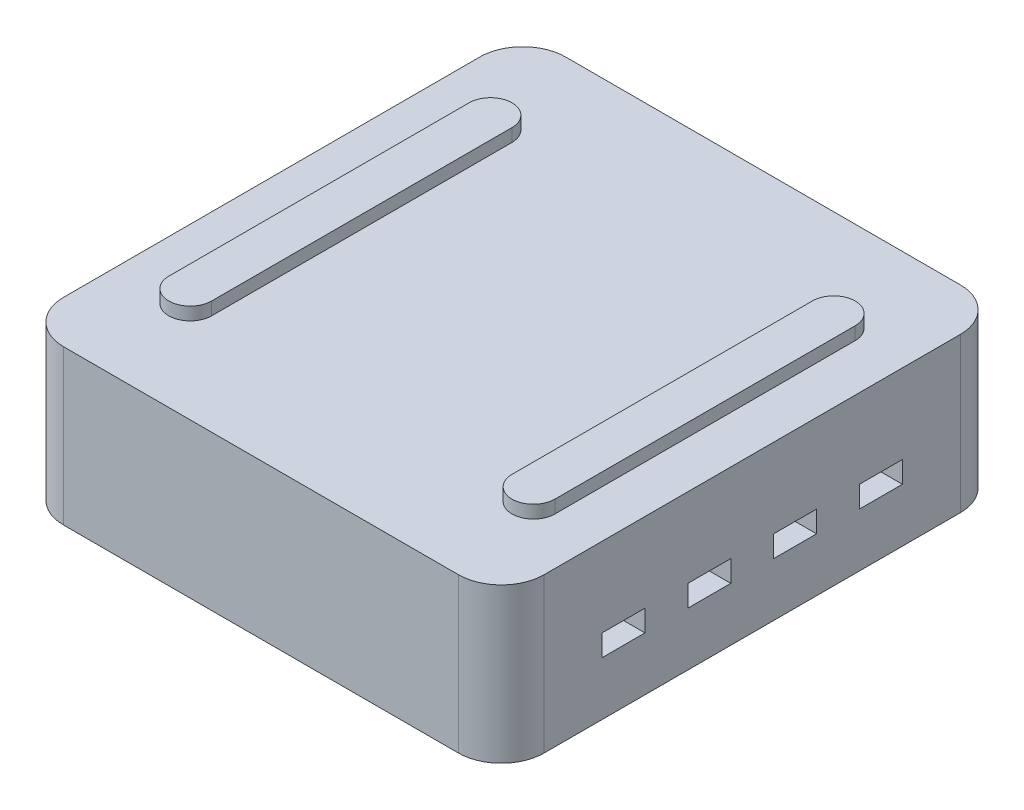
SolidWorks part; units mm, degrees
ref_plane "前视基准面" through (0, 0, 0) normal (0, 0, 1) x (1, 0, 0)
ref_plane "上视基准面" through (0, 0, 0) normal (0, 1, 0) x (1, 0, 0)
ref_plane "右视基准面" through (0, 0, 0) normal (1, 0, 0) x (0, 0, -1)
other "Configuration Table"
sketch "草图1" plane through (0, 0, 0) normal (0, 1, 0) x (1, 0, 0)
  line L1 (-56, 58.5) -> (56, 58.5)
  line L2 (-56, 58.5) -> (-56, -58.5)
  line L3 (-56, -58.5) -> (56, -58.5)
  line L4 (56, 58.5) -> (56, -58.5)
  line L5 (-56, 58.5) -> (56, -58.5) construction
  line L6 (-56, -58.5) -> (56, 58.5) construction
  point P0 (0, 0)
  dimension "D1" = 112
  dimension "D2" = 117
extrude "凸台-拉伸1" add sketch "草图1" along normal blind 36
fillet "圆角1" radius 10 4 edges at (-56, 18, 58.5) (-56, 18, -58.5) (56, 18, -58.5) (56, 18, 58.5)
sketch "草图3" plane through (0, 36, 0) normal (0, 1, 0) x (1, 0, 0)
  line L0 (-40, 35) -> (-40, -35) construction
  line L1 (-35, 35) -> (-35, -35)
  line L2 (-45, 35) -> (-45, -35)
  line L3 (0, 0) -> (-40, 0) construction
  line L4 (0, 0) -> (0, 58.5) construction
  line L5 (46, 58.5) -> (-46, 58.5) construction
  line L6 (40, 35) -> (40, -35) construction
  line L7 (35, 35) -> (35, -35)
  line L8 (45, 35) -> (45, -35)
  arc A0 (-35, 35) -> (-45, 35) centre (-40, 35) ccw
  arc A1 (-45, -35) -> (-35, -35) centre (-40, -35) ccw
  arc A2 (35, 35) -> (45, 35) centre (40, 35) cw
  arc A3 (45, -35) -> (35, -35) centre (40, -35) cw
  point P2 (-40, 0)
  point P15 (40, 0)
  dimension "D1" = 5
  dimension "D2" = 40
  dimension "D3" = 70
extrude "凸台-拉伸2" add sketch "草图3" along normal blind 3
sketch "草图4" plane through (-56, 0, 0) normal (-1, 0, 0) x (0, 0, 1)
  line L0 (-15, 17.5) -> (-15, 12.5)
  line L17 (-35, 17.5) -> (-25, 17.5)
  line L18 (-35, 17.5) -> (-35, 12.5)
  line L19 (-35, 12.5) -> (-25, 12.5)
  line L20 (-25, 17.5) -> (-25, 12.5)
  line L21 (-15, 17.5) -> (-5, 17.5)
  line L22 (-5, 17.5) -> (-5, 12.5)
  line L23 (-15, 12.5) -> (-5, 12.5)
  line L24 (5, 17.5) -> (5, 12.5)
  line L25 (5, 17.5) -> (15, 17.5)
  line L26 (15, 17.5) -> (15, 12.5)
  line L27 (5, 12.5) -> (15, 12.5)
  line L28 (25, 17.5) -> (25, 12.5)
  line L29 (25, 17.5) -> (35, 17.5)
  line L30 (35, 17.5) -> (35, 12.5)
  line L31 (25, 12.5) -> (35, 12.5)
  line L32 (-5, 15) -> (5, 15) construction
  line L33 (0, 0) -> (0, 15) construction
  dimension "D2" = 10
  dimension "D3" = 5
  dimension "D4" = 10
  dimension "D5" = 15
  dimension "D1" = 4
extrude "切除-拉伸1" cut sketch "草图4" against normal blind 10
fillet "圆角2" radius 1 16 edges at (-51, 12.5, 25) (-51, 17.5, 35) (-51, 17.5, 25) (-51, 12.5, 5) (-51, 12.5, 15) (-51, 17.5, 15) (-51, 17.5, 5) (-51, 12.5, -15) (-51, 12.5, -5) (-51, 17.5, -5) (-51, 17.5, -15) (-51, 12.5, -25) (-51, 17.5, -25) (-51, 17.5, -35) (-51, 12.5, -35) (-51, 12.5, 35)
sketch "草图5" plane through (56, 0, 0) normal (1, 0, 0) x (0, 0, -1)
  line L0 (-15, 17.5) -> (-15, 12.5)
  line L1 (-35, 17.5) -> (-25, 17.5)
  line L2 (-35, 17.5) -> (-35, 12.5)
  line L3 (-35, 12.5) -> (-25, 12.5)
  line L4 (-25, 17.5) -> (-25, 12.5)
  line L5 (-15, 17.5) -> (-5, 17.5)
  line L6 (-5, 17.5) -> (-5, 12.5)
  line L7 (-15, 12.5) -> (-5, 12.5)
  line L8 (5, 17.5) -> (5, 12.5)
  line L9 (5, 17.5) -> (15, 17.5)
  line L10 (15, 17.5) -> (15, 12.5)
  line L11 (5, 12.5) -> (15, 12.5)
  line L12 (25, 17.5) -> (25, 12.5)
  line L13 (25, 17.5) -> (35, 17.5)
  line L14 (35, 17.5) -> (35, 12.5)
  line L15 (25, 12.5) -> (35, 12.5)
  line L16 (-5, 15) -> (5, 15) construction
  line L17 (0, 0) -> (0, 15) construction
  line L18 (-48.5, 0) -> (48.5, 0) construction
  dimension "D1" = 10
  dimension "D2" = 5
  dimension "D4" = 15
  dimension "D5" = 10
  dimension "D3" = 4
extrude "切除-拉伸2" cut sketch "草图5" against normal blind 10
